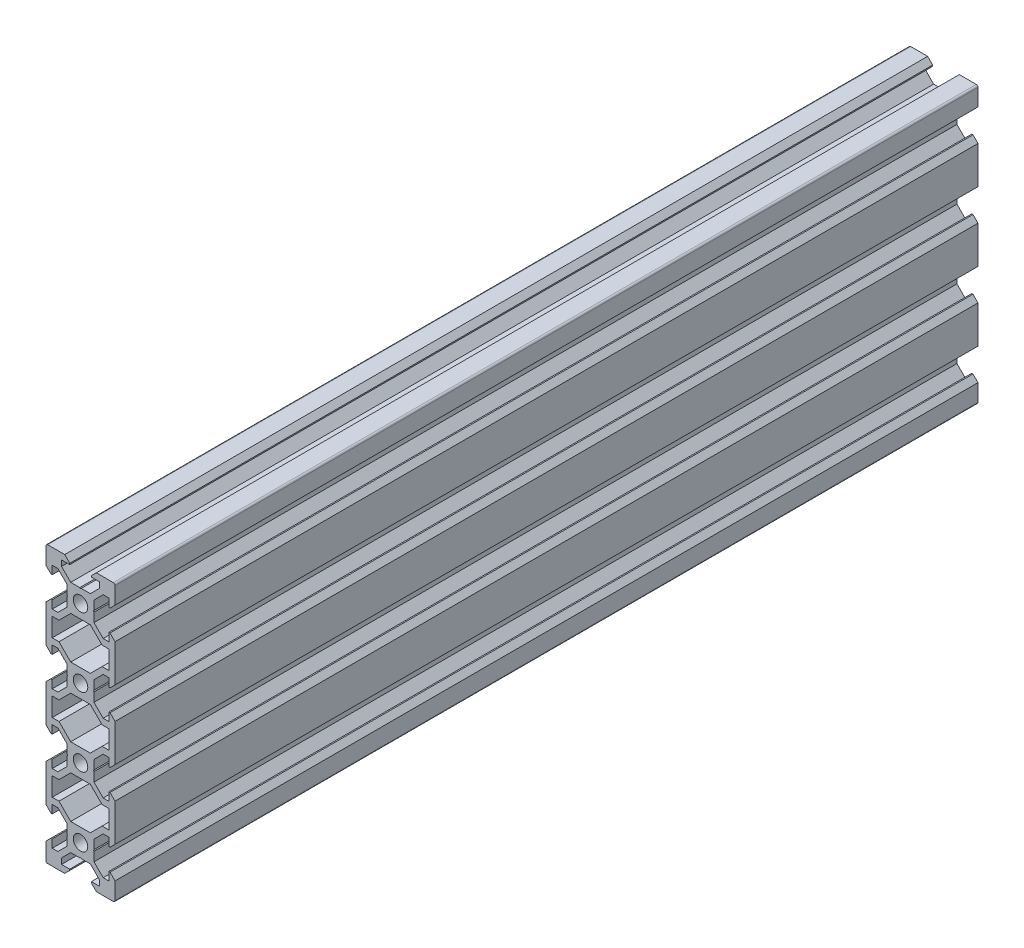
SolidWorks part; units mm, degrees
material "6061-T6 (SS)"
ref_plane "Front Plane" through (0, 0, 0) normal (0, 0, 1) x (1, 0, 0)
ref_plane "Top Plane" through (0, 0, 0) normal (0, 1, 0) x (1, 0, 0)
ref_plane "Right Plane" through (0, 0, 0) normal (1, 0, 0) x (0, 0, -1)
sketch "Sketch1" plane through (0, 0, 0) normal (0, 0, 1) x (1, 0, 0)
  line L0 (0, 0) -> (10, 0) construction
  line L1 (9.5, -40) -> (-9.5, -40)
  line L2 (10, -39.5) -> (10, 39.5)
  line L3 (9.5, 40) -> (-9.5, 40)
  line L4 (-10, -39.5) -> (-10, 39.5)
  line L5 (10, -40) -> (-10, 40) construction
  line L6 (10, 40) -> (-10, -40) construction
  circle A0 centre (0, 30) radius 2.1
  circle A1 centre (0, 10) radius 2.1
  circle A2 centre (0, -10) radius 2.1
  circle A3 centre (0, -30) radius 2.1
  arc A4 (-9.5, -40) -> (-10, -39.5) centre (-9.5, -39.5) cw
  arc A5 (9.5, -40) -> (10, -39.5) centre (9.5, -39.5) ccw
  arc A6 (10, 39.5) -> (9.5, 40) centre (9.5, 39.5) ccw
  arc A7 (-9.5, 40) -> (-10, 39.5) centre (-9.5, 39.5) ccw
  point P0 (0, 0)
  line B0 (0, 30) -> (0, 40) construction
  line B1 (0, 33.69) -> (-0.21, 33.9)
  line B2 (-0.21, 33.9) -> (-2.8393, 33.9)
  line B3 (-2.8393, 33.9) -> (-5.5, 36.5607)
  line B4 (-5.5, 36.5607) -> (-5.5, 38.2)
  line B5 (-5.5, 38.2) -> (-3.125, 38.2)
  line B6 (-3.125, 38.2) -> (-3.125, 38.545)
  line B7 (-3.125, 38.545) -> (-4.58, 40)
  line B8 (-4.58, 40) -> (4.58, 40)
  line B9 (0, 30) -> (-5.9132, 35.9132) construction
  line B10 (3.125, 38.545) -> (4.58, 40)
  line B11 (3.125, 38.2) -> (3.125, 38.545)
  line B12 (5.5, 38.2) -> (3.125, 38.2)
  line B13 (5.5, 36.5607) -> (5.5, 38.2)
  line B14 (2.8393, 33.9) -> (5.5, 36.5607)
  line B15 (0.21, 33.9) -> (2.8393, 33.9)
  line B16 (0, 33.69) -> (0.21, 33.9)
  line B17 (0, 30) -> (-10, 30) construction
  line B18 (-3.69, 30) -> (-3.9, 29.79)
  line B19 (-3.9, 29.79) -> (-3.9, 27.1607)
  line B20 (-3.9, 27.1607) -> (-6.5607, 24.5)
  line B21 (-6.5607, 24.5) -> (-8.2, 24.5)
  line B22 (-8.2, 24.5) -> (-8.2, 26.875)
  line B23 (-8.2, 26.875) -> (-8.545, 26.875)
  line B24 (-8.545, 26.875) -> (-10, 25.42)
  line B25 (-10, 25.42) -> (-10, 34.58)
  line B26 (0, 30) -> (-5.9132, 24.0868) construction
  line B27 (-8.545, 33.125) -> (-10, 34.58)
  line B28 (-8.2, 33.125) -> (-8.545, 33.125)
  line B29 (-8.2, 35.5) -> (-8.2, 33.125)
  line B30 (-6.5607, 35.5) -> (-8.2, 35.5)
  line B31 (-3.9, 32.8393) -> (-6.5607, 35.5)
  line B32 (-3.9, 30.21) -> (-3.9, 32.8393)
  line B33 (-3.69, 30) -> (-3.9, 30.21)
  line B34 (0, 10) -> (-10, 10) construction
  line B35 (-3.69, 10) -> (-3.9, 9.79)
  line B36 (-3.9, 9.79) -> (-3.9, 7.1607)
  line B37 (-3.9, 7.1607) -> (-6.5607, 4.5)
  line B38 (-6.5607, 4.5) -> (-8.2, 4.5)
  line B39 (-8.2, 4.5) -> (-8.2, 6.875)
  line B40 (-8.2, 6.875) -> (-8.545, 6.875)
  line B41 (-8.545, 6.875) -> (-10, 5.42)
  line B42 (-10, 5.42) -> (-10, 14.58)
  line B43 (0, 10) -> (-5.9132, 4.0868) construction
  line B44 (-8.545, 13.125) -> (-10, 14.58)
  line B45 (-8.2, 13.125) -> (-8.545, 13.125)
  line B46 (-8.2, 15.5) -> (-8.2, 13.125)
  line B47 (-6.5607, 15.5) -> (-8.2, 15.5)
  line B48 (-3.9, 12.8393) -> (-6.5607, 15.5)
  line B49 (-3.9, 10.21) -> (-3.9, 12.8393)
  line B50 (-3.69, 10) -> (-3.9, 10.21)
  line B51 (0, -10) -> (-10, -10) construction
  line B52 (-3.69, -10) -> (-3.9, -10.21)
  line B53 (-3.9, -10.21) -> (-3.9, -12.8393)
  line B54 (-3.9, -12.8393) -> (-6.5607, -15.5)
  line B55 (-6.5607, -15.5) -> (-8.2, -15.5)
  line B56 (-8.2, -15.5) -> (-8.2, -13.125)
  line B57 (-8.2, -13.125) -> (-8.545, -13.125)
  line B58 (-8.545, -13.125) -> (-10, -14.58)
  line B59 (-10, -14.58) -> (-10, -5.42)
  line B60 (0, -10) -> (-5.9132, -15.9132) construction
  line B61 (-8.545, -6.875) -> (-10, -5.42)
  line B62 (-8.2, -6.875) -> (-8.545, -6.875)
  line B63 (-8.2, -4.5) -> (-8.2, -6.875)
  line B64 (-6.5607, -4.5) -> (-8.2, -4.5)
  line B65 (-3.9, -7.1607) -> (-6.5607, -4.5)
  line B66 (-3.9, -9.79) -> (-3.9, -7.1607)
  line B67 (-3.69, -10) -> (-3.9, -9.79)
  line B68 (0, -30) -> (-10, -30) construction
  line B69 (-3.69, -30) -> (-3.9, -30.21)
  line B70 (-3.9, -30.21) -> (-3.9, -32.8393)
  line B71 (-3.9, -32.8393) -> (-6.5607, -35.5)
  line B72 (-6.5607, -35.5) -> (-8.2, -35.5)
  line B73 (-8.2, -35.5) -> (-8.2, -33.125)
  line B74 (-8.2, -33.125) -> (-8.545, -33.125)
  line B75 (-8.545, -33.125) -> (-10, -34.58)
  line B76 (-10, -34.58) -> (-10, -25.42)
  line B77 (0, -30) -> (-5.9132, -35.9132) construction
  line B78 (-8.545, -26.875) -> (-10, -25.42)
  line B79 (-8.2, -26.875) -> (-8.545, -26.875)
  line B80 (-8.2, -24.5) -> (-8.2, -26.875)
  line B81 (-6.5607, -24.5) -> (-8.2, -24.5)
  line B82 (-3.9, -27.1607) -> (-6.5607, -24.5)
  line B83 (-3.9, -29.79) -> (-3.9, -27.1607)
  line B84 (-3.69, -30) -> (-3.9, -29.79)
  line B85 (0, -30) -> (0, -40) construction
  line B86 (0, -33.69) -> (0.21, -33.9)
  line B87 (0.21, -33.9) -> (2.8393, -33.9)
  line B88 (2.8393, -33.9) -> (5.5, -36.5607)
  line B89 (5.5, -36.5607) -> (5.5, -38.2)
  line B90 (5.5, -38.2) -> (3.125, -38.2)
  line B91 (3.125, -38.2) -> (3.125, -38.545)
  line B92 (3.125, -38.545) -> (4.58, -40)
  line B93 (4.58, -40) -> (-4.58, -40)
  line B94 (0, -30) -> (5.9132, -35.9132) construction
  line B95 (-3.125, -38.545) -> (-4.58, -40)
  line B96 (-3.125, -38.2) -> (-3.125, -38.545)
  line B97 (-5.5, -38.2) -> (-3.125, -38.2)
  line B98 (-5.5, -36.5607) -> (-5.5, -38.2)
  line B99 (-2.8393, -33.9) -> (-5.5, -36.5607)
  line B100 (-0.21, -33.9) -> (-2.8393, -33.9)
  line B101 (0, -33.69) -> (-0.21, -33.9)
  line B102 (0, -30) -> (10, -30) construction
  line B103 (3.69, -30) -> (3.9, -29.79)
  line B104 (3.9, -29.79) -> (3.9, -27.1607)
  line B105 (3.9, -27.1607) -> (6.5607, -24.5)
  line B106 (6.5607, -24.5) -> (8.2, -24.5)
  line B107 (8.2, -24.5) -> (8.2, -26.875)
  line B108 (8.2, -26.875) -> (8.545, -26.875)
  line B109 (8.545, -26.875) -> (10, -25.42)
  line B110 (10, -25.42) -> (10, -34.58)
  line B111 (0, -30) -> (5.9132, -24.0868) construction
  line B112 (8.545, -33.125) -> (10, -34.58)
  line B113 (8.2, -33.125) -> (8.545, -33.125)
  line B114 (8.2, -35.5) -> (8.2, -33.125)
  line B115 (6.5607, -35.5) -> (8.2, -35.5)
  line B116 (3.9, -32.8393) -> (6.5607, -35.5)
  line B117 (3.9, -30.21) -> (3.9, -32.8393)
  line B118 (3.69, -30) -> (3.9, -30.21)
  line B119 (0, -10) -> (10, -10) construction
  line B120 (3.69, -10) -> (3.9, -9.79)
  line B121 (3.9, -9.79) -> (3.9, -7.1607)
  line B122 (3.9, -7.1607) -> (6.5607, -4.5)
  line B123 (6.5607, -4.5) -> (8.2, -4.5)
  line B124 (8.2, -4.5) -> (8.2, -6.875)
  line B125 (8.2, -6.875) -> (8.545, -6.875)
  line B126 (8.545, -6.875) -> (10, -5.42)
  line B127 (10, -5.42) -> (10, -14.58)
  line B128 (0, -10) -> (5.9132, -4.0868) construction
  line B129 (8.545, -13.125) -> (10, -14.58)
  line B130 (8.2, -13.125) -> (8.545, -13.125)
  line B131 (8.2, -15.5) -> (8.2, -13.125)
  line B132 (6.5607, -15.5) -> (8.2, -15.5)
  line B133 (3.9, -12.8393) -> (6.5607, -15.5)
  line B134 (3.9, -10.21) -> (3.9, -12.8393)
  line B135 (3.69, -10) -> (3.9, -10.21)
  line B136 (0, 10) -> (10, 10) construction
  line B137 (3.69, 10) -> (3.9, 10.21)
  line B138 (3.9, 10.21) -> (3.9, 12.8393)
  line B139 (3.9, 12.8393) -> (6.5607, 15.5)
  line B140 (6.5607, 15.5) -> (8.2, 15.5)
  line B141 (8.2, 15.5) -> (8.2, 13.125)
  line B142 (8.2, 13.125) -> (8.545, 13.125)
  line B143 (8.545, 13.125) -> (10, 14.58)
  line B144 (10, 14.58) -> (10, 5.42)
  line B145 (0, 10) -> (5.9132, 15.9132) construction
  line B146 (8.545, 6.875) -> (10, 5.42)
  line B147 (8.2, 6.875) -> (8.545, 6.875)
  line B148 (8.2, 4.5) -> (8.2, 6.875)
  line B149 (6.5607, 4.5) -> (8.2, 4.5)
  line B150 (3.9, 7.1607) -> (6.5607, 4.5)
  line B151 (3.9, 9.79) -> (3.9, 7.1607)
  line B152 (3.69, 10) -> (3.9, 9.79)
  line B153 (0, 30) -> (10, 30) construction
  line B154 (3.69, 30) -> (3.9, 30.21)
  line B155 (3.9, 30.21) -> (3.9, 32.8393)
  line B156 (3.9, 32.8393) -> (6.5607, 35.5)
  line B157 (6.5607, 35.5) -> (8.2, 35.5)
  line B158 (8.2, 35.5) -> (8.2, 33.125)
  line B159 (8.2, 33.125) -> (8.545, 33.125)
  line B160 (8.545, 33.125) -> (10, 34.58)
  line B161 (10, 34.58) -> (10, 25.42)
  line B162 (0, 30) -> (5.9132, 35.9132) construction
  line B163 (8.545, 26.875) -> (10, 25.42)
  line B164 (8.2, 26.875) -> (8.545, 26.875)
  line B165 (8.2, 24.5) -> (8.2, 26.875)
  line B166 (6.5607, 24.5) -> (8.2, 24.5)
  line B167 (3.9, 27.1607) -> (6.5607, 24.5)
  line B168 (3.9, 29.79) -> (3.9, 27.1607)
  line B169 (3.69, 30) -> (3.9, 29.79)
  line B170 (-8.2, 17.3) -> (-8.2, 22.7)
  line B171 (-8.2, 22.7) -> (-6.2393, 22.7)
  line B172 (-6.2393, 22.7) -> (-2.8393, 26.1)
  line B173 (-2.8393, 26.1) -> (2.8393, 26.1)
  line B174 (0, 26.1) -> (0, 20) construction
  line B175 (0, 20) -> (-8.2, 20) construction
  line B176 (6.2393, 22.7) -> (2.8393, 26.1)
  line B177 (8.2, 22.7) -> (6.2393, 22.7)
  line B178 (8.2, 17.3) -> (8.2, 22.7)
  line B179 (8.2, 17.3) -> (6.2393, 17.3)
  line B180 (6.2393, 17.3) -> (2.8393, 13.9)
  line B181 (-2.8393, 13.9) -> (2.8393, 13.9)
  line B182 (-6.2393, 17.3) -> (-2.8393, 13.9)
  line B183 (-8.2, 17.3) -> (-6.2393, 17.3)
  line B184 (0, 26.1) -> (0, 30) construction
  line B185 (0, 30) -> (-5.0927, 24.9073) construction
  line B186 (-8.2, -2.7) -> (-8.2, 2.7)
  line B187 (-8.2, 2.7) -> (-6.2393, 2.7)
  line B188 (-6.2393, 2.7) -> (-2.8393, 6.1)
  line B189 (-2.8393, 6.1) -> (2.8393, 6.1)
  line B190 (0, 6.1) -> (0, 0) construction
  line B191 (0, 0) -> (-8.2, 0) construction
  line B192 (6.2393, 2.7) -> (2.8393, 6.1)
  line B193 (8.2, 2.7) -> (6.2393, 2.7)
  line B194 (8.2, -2.7) -> (8.2, 2.7)
  line B195 (8.2, -2.7) -> (6.2393, -2.7)
  line B196 (6.2393, -2.7) -> (2.8393, -6.1)
  line B197 (-2.8393, -6.1) -> (2.8393, -6.1)
  line B198 (-6.2393, -2.7) -> (-2.8393, -6.1)
  line B199 (-8.2, -2.7) -> (-6.2393, -2.7)
  line B200 (0, 6.1) -> (0, 10) construction
  line B201 (0, 10) -> (-5.0927, 4.9073) construction
  line B202 (-8.2, -22.7) -> (-8.2, -17.3)
  line B203 (-8.2, -17.3) -> (-6.2393, -17.3)
  line B204 (-6.2393, -17.3) -> (-2.8393, -13.9)
  line B205 (-2.8393, -13.9) -> (2.8393, -13.9)
  line B206 (0, -13.9) -> (0, -20) construction
  line B207 (0, -20) -> (-8.2, -20) construction
  line B208 (6.2393, -17.3) -> (2.8393, -13.9)
  line B209 (8.2, -17.3) -> (6.2393, -17.3)
  line B210 (8.2, -22.7) -> (8.2, -17.3)
  line B211 (8.2, -22.7) -> (6.2393, -22.7)
  line B212 (6.2393, -22.7) -> (2.8393, -26.1)
  line B213 (-2.8393, -26.1) -> (2.8393, -26.1)
  line B214 (-6.2393, -22.7) -> (-2.8393, -26.1)
  line B215 (-8.2, -22.7) -> (-6.2393, -22.7)
  line B216 (0, -13.9) -> (0, -10) construction
  line B217 (0, -10) -> (-5.0927, -15.0927) construction
  dimension "D5" = 4.2
  dimension "D6" = 0.5
  dimension "D1" = 20
  dimension "D2" = 80
  dimension "D3" = 20
  dimension "D4" = 20
sketch_block_instance "V Slot 1-4"
sketch_block "V Slot 1" parameters "D1"=10, "D2"=11, "D3"=4.3, "D4"=1.8, "D5"=0.21, "D6"=45, "D7"=9.16, "D8"=1.5, "D9"=6.25
sketch_block_instance "V Slot 1-5"
sketch_block_instance "V Slot 1-6"
sketch_block_instance "V Slot 1-7"
sketch_block_instance "V Slot 1-8"
sketch_block_instance "V Slot 1-9"
sketch_block_instance "V Slot 1-10"
sketch_block_instance "V Slot 1-11"
sketch_block_instance "V Slot 1-12"
sketch_block_instance "V Slot 1-13"
sketch_block_instance "Center Cutout 1-1"
sketch_block "Center Cutout 1" parameters "D1"=5.4, "D2"=12.2, "D3"=8.2, "D4"=45, "D5"=10, "D6"=1.5
sketch_block_instance "Center Cutout 1-2"
sketch_block_instance "Center Cutout 1-3"
extrude "Boss-Extrude1" add sketch "Sketch1" along normal blind 250 contours B169 B154 B155 B156 B157 B158 B159 B160 L2 A6 L3 B10 B11 B12 B13 B14 B15 B16 B1 B2 B3 B4 B5 B6 B7 A7 L4 B27 B28 B29 B30 B31 B32 B33 B18 B19 B20 B21 B22 B23 B24 B44 B45 B46 B47 B48 B49 B50 B35
